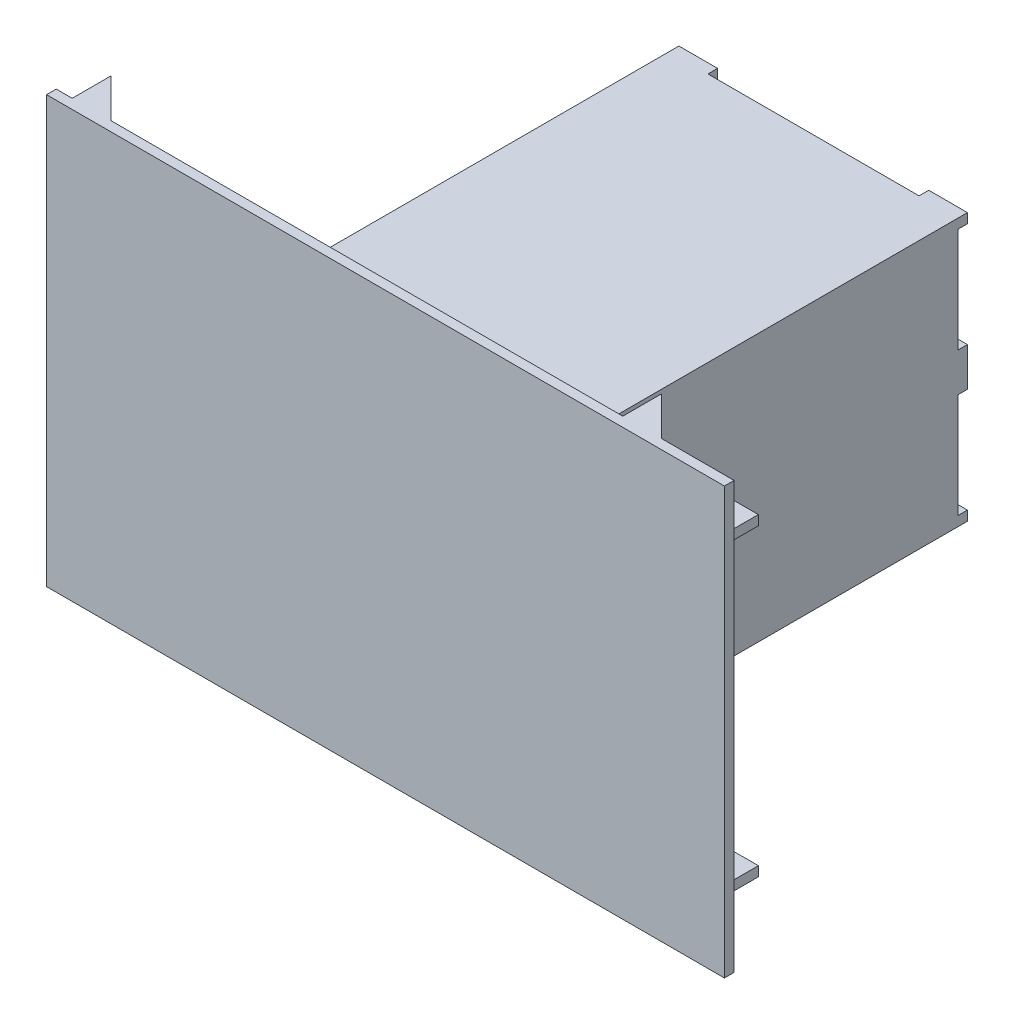
SolidWorks part; units mm, degrees
ref_plane "前视基准面" through (0, 0, 0) normal (0, 0, 1) x (1, 0, 0)
ref_plane "上视基准面" through (0, 0, 0) normal (0, 1, 0) x (1, 0, 0)
ref_plane "右视基准面" through (0, 0, 0) normal (1, 0, 0) x (0, 0, -1)
other "Configuration Table"
sketch "草图1" plane through (0, 0, 0) normal (0, 0, 1) x (1, 0, 0)
  line L0 (-60.5909, 0) -> (14.201, 0) construction
  line L1 (0, 25.976) -> (0, -21.0056) construction
  line L2 (66.5, -61) -> (4, -61)
  line L3 (-74.5, -69) -> (74.5, -69)
  line L4 (-74.5, -69) -> (-74.5, 69)
  line L5 (-74.5, 69) -> (74.5, 69)
  line L6 (74.5, -69) -> (74.5, 69)
  line L7 (-74.5, -69) -> (74.5, 69) construction
  line L8 (-74.5, 69) -> (74.5, -69) construction
  line L9 (-66.5, 61) -> (-4, 61)
  line L10 (-66.5, 61) -> (-66.5, -61)
  line L11 (-66.5, -61) -> (-4, -61)
  line L12 (-4, 61) -> (-4, -61)
  line L13 (4, 61) -> (4, -61)
  line L14 (66.5, 61) -> (4, 61)
  line L15 (66.5, 61) -> (66.5, -61)
  point P4 (0, 0)
  dimension "D1" = 149
  dimension "D2" = 138
  dimension "D3" = 8
  dimension "D4" = 8
  dimension "D5" = 8
extrude "凸台-拉伸1" add sketch "草图1" along normal blind 216
sketch "草图2" plane through (0, 0, 0) normal (0, 0, -1) x (-1, 0, 0)
  line L5 (74.5, 69) -> (74.5, -69) construction
  line L6 (74.5, 10) -> (69.5, 10)
  line L7 (74.5, 10) -> (74.5, -10)
  line L8 (74.5, -10) -> (69.5, -10)
  line L9 (69.5, 10) -> (69.5, -10)
  line L10 (-88.8421, 0) -> (129.204, 0) construction
  line L11 (0, 87.2221) -> (0, -106.4348) construction
  line L16 (-74.5, -10) -> (-69.5, -10)
  line L17 (-69.5, 10) -> (-69.5, -10)
  line L18 (-74.5, 10) -> (-69.5, 10)
  line L19 (-74.5, 10) -> (-74.5, -10)
  line L20 (74.5, 64) -> (54.5, 64)
  line L21 (-74.5, 69) -> (-54.5, 69)
  line L22 (-74.5, 69) -> (-74.5, 64)
  line L23 (-74.5, 64) -> (-54.5, 64)
  line L24 (-54.5, 69) -> (-54.5, 64)
  line L25 (54.5, 69) -> (54.5, 64)
  line L26 (74.5, 69) -> (54.5, 69)
  line L27 (74.5, 69) -> (74.5, 64)
  line L28 (74.5, -69) -> (74.5, -64)
  line L29 (74.5, -69) -> (54.5, -69)
  line L30 (54.5, -69) -> (54.5, -64)
  line L31 (74.5, -64) -> (54.5, -64)
  line L32 (-74.5, -64) -> (-54.5, -64)
  line L33 (-54.5, -69) -> (-54.5, -64)
  line L34 (-74.5, -69) -> (-54.5, -69)
  line L35 (-74.5, -69) -> (-74.5, -64)
  dimension "D1" = 5
  dimension "D2" = 5
  dimension "D3" = 20
  dimension "D4" = 20
extrude "凸台-拉伸2" add sketch "草图2" along normal blind 5
sketch "草图3" plane through (0, 0, 216) normal (0, 0, 1) x (1, 0, 0)
  line L5 (-175, -110) -> (175, -110)
  line L6 (-175, -110) -> (-175, 110)
  line L7 (-175, 110) -> (175, 110)
  line L8 (175, -110) -> (175, 110)
  line L9 (-175, -110) -> (175, 110) construction
  line L10 (-175, 110) -> (175, -110) construction
  point P0 (0, 0)
  point P6 (23.12, -2.7468)
  point P7 (0, 0)
  point P9 (0, 0)
  dimension "D1" = 350
  dimension "D2" = 220
extrude "凸台-拉伸3" add sketch "草图3" along normal blind 5
sketch "草图5" plane through (0, 69, 0) normal (0, 1, 0) x (1, 0, 0)
  line L0 (-146.7541, -216) -> (-166.7541, -196)
  line L1 (175, -216) -> (-175, -216) construction
  line L2 (-166.7541, -196) -> (-166.7541, -216)
  line L3 (-166.7541, -216) -> (-146.7541, -216)
  line L4 (117.5459, -216) -> (137.5459, -216)
  line L5 (137.5459, -216) -> (117.5459, -196)
  line L6 (117.5459, -196) -> (117.5459, -216)
  line L7 (-166.7541, -216) -> (117.5459, -216) construction
  dimension "D1" = 45
  dimension "D2" = 20
  dimension "D3" = 2
  dimension "D4" = 284.3
extrude "凸台-拉伸4" add sketch "草图5" along normal blind 29 from offset 12
sketch "草图6" plane through (0, 81, 0) normal (0, -1, 0) x (1, 0, 0)
  line L0 (117.5459, 216) -> (167.5459, 216)
  line L1 (-166.7541, 216) -> (-116.7541, 216)
  line L2 (-166.7541, 216) -> (-166.7541, 196)
  line L3 (-166.7541, 196) -> (-116.7541, 196)
  line L4 (-116.7541, 216) -> (-116.7541, 196)
  line L5 (117.5459, 216) -> (117.5459, 196)
  line L6 (117.5459, 196) -> (167.5459, 196)
  line L7 (167.5459, 216) -> (167.5459, 196)
  line L8 (-166.7541, 216) -> (117.5459, 216) construction
  dimension "D1" = 50
  dimension "D3" = 284.3
  dimension "D2" = 2
extrude "凸台-拉伸5" add sketch "草图6" along normal blind 5
mirror "镜向1" about plane through (0, 0, 0) normal (0, 1, 0) of "凸台-拉伸5", "凸台-拉伸4"
